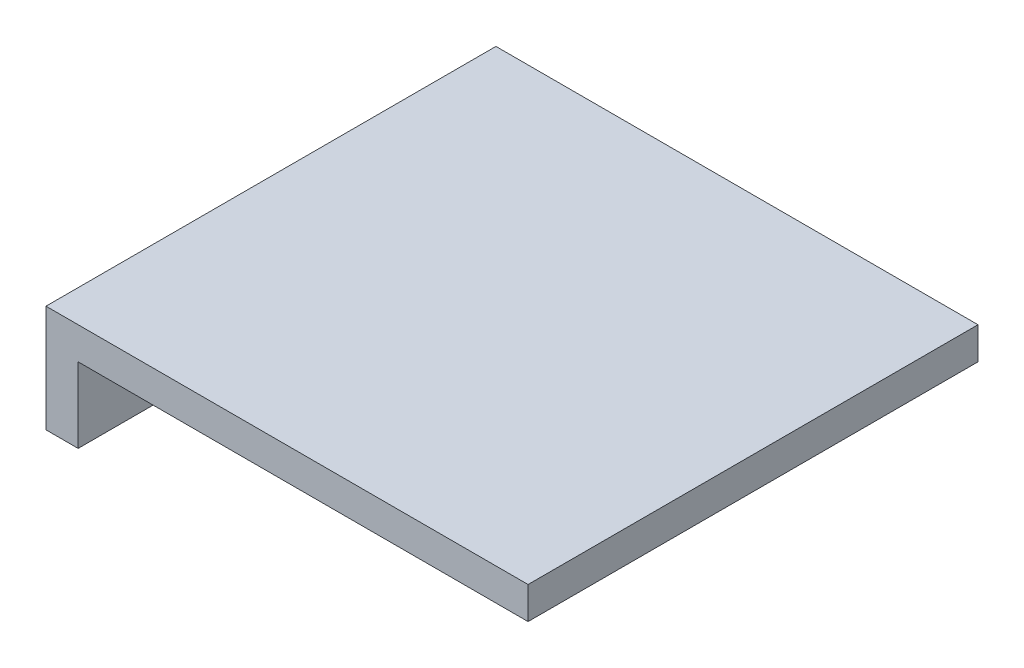
SolidWorks part; units mm, degrees
ref_plane "Front Plane" through (0, 0, 0) normal (0, 0, 1) x (1, 0, 0)
ref_plane "Top Plane" through (0, 0, 0) normal (0, 1, 0) x (1, 0, 0)
ref_plane "Right Plane" through (0, 0, 0) normal (1, 0, 0) x (0, 0, -1)
sketch "Sketch1" plane through (0, 0, 0) normal (0, 0, 1) x (1, 0, 0)
  line L0 (-3, 0) -> (-3, 10)
  line L1 (-3, 10) -> (42, 10)
  line L2 (0, 0) -> (0, 7)
  line L3 (0, 7) -> (42, 7)
  line L4 (-3, 0) -> (0, 0)
  line L5 (42, 10) -> (42, 7)
  dimension "D1" = 7
  dimension "D2" = 42
  dimension "D3" = 3
extrude "Boss-Extrude1" add sketch "Sketch1" along normal blind 42
